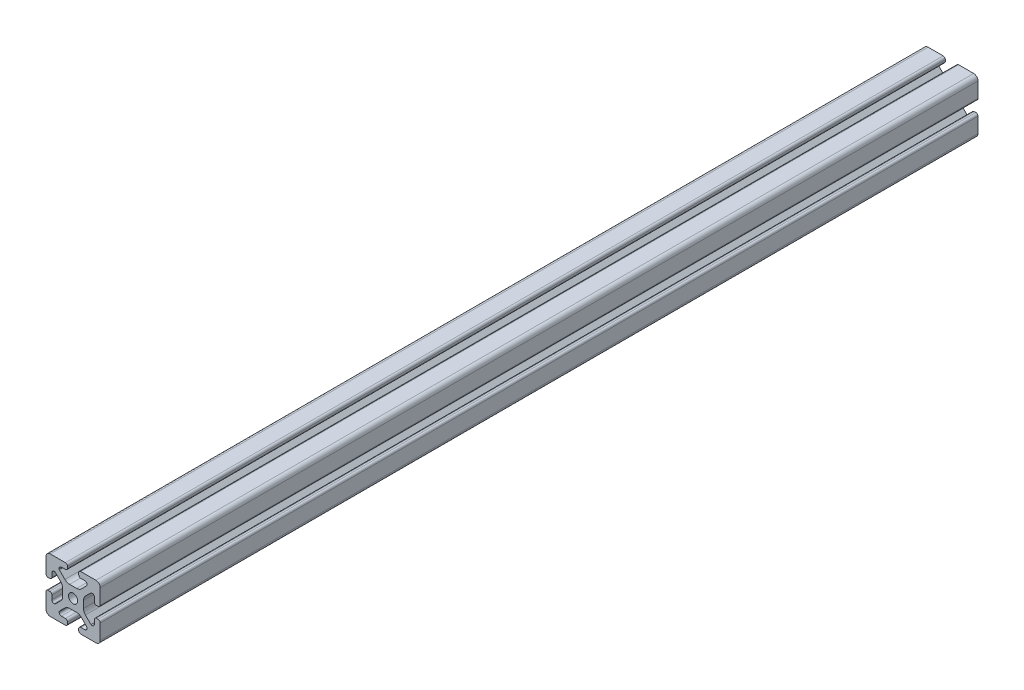
SolidWorks part; units mm, degrees
ref_plane "Front Plane" through (0, 0, 0) normal (0, 0, 1) x (1, 0, 0)
ref_plane "Top Plane" through (0, 0, 0) normal (0, 1, 0) x (1, 0, 0)
ref_plane "Right Plane" through (0, 0, 0) normal (1, 0, 0) x (0, 0, -1)
ref_plane "Plane1" through (0, 0, -4000) normal (0, 0, -1) x (-1, 0, 0)
sketch "Sketch1" plane through (0, 0, -4000) normal (0, 0, -1) x (-1, 0, 0)
  line L0 (16.83, 20) -> (5.6904, 20)
  line L1 (4.1204, 18.43) -> (4.1204, 17.25)
  line L2 (5.6904, 15.68) -> (8.7154, 15.68)
  line L3 (10.2854, 14.11) -> (10.2854, 13.6549)
  line L4 (10.0628, 13.1175) -> (6.0551, 9.1098)
  line L5 (2.6153, 7.685) -> (-2.6153, 7.685)
  line L6 (-6.0551, 9.1098) -> (-10.0628, 13.1175)
  line L7 (-10.2854, 13.6549) -> (-10.2854, 14.11)
  line L8 (-8.7154, 15.68) -> (-5.6904, 15.68)
  line L9 (-4.1204, 17.25) -> (-4.1204, 18.43)
  line L10 (-5.6904, 20) -> (-16.83, 20)
  line L11 (-20, 16.83) -> (-20, 5.6904)
  line L12 (-18.43, 4.1204) -> (-17.25, 4.1204)
  line L13 (-15.68, 5.6904) -> (-15.68, 8.7154)
  line L14 (-14.11, 10.2854) -> (-13.6549, 10.2854)
  line L15 (-13.1175, 10.0628) -> (-9.1098, 6.0551)
  line L16 (-7.685, 2.6153) -> (-7.685, -2.6153)
  line L17 (-9.1098, -6.0551) -> (-13.1175, -10.0628)
  line L18 (-13.6549, -10.2854) -> (-14.11, -10.2854)
  line L19 (-15.68, -8.7154) -> (-15.68, -5.6904)
  line L20 (-17.25, -4.1204) -> (-18.43, -4.1204)
  line L21 (-20, -5.6904) -> (-20, -16.83)
  line L22 (-16.83, -20) -> (-5.6904, -20)
  line L23 (-4.1204, -18.43) -> (-4.1204, -17.25)
  line L24 (-5.6904, -15.68) -> (-8.7154, -15.68)
  line L25 (-10.2854, -14.11) -> (-10.2854, -13.6549)
  line L26 (-10.0628, -13.1175) -> (-6.0551, -9.1098)
  line L27 (-2.6153, -7.685) -> (2.6153, -7.685)
  line L28 (6.0551, -9.1098) -> (10.0628, -13.1175)
  line L29 (10.2854, -13.6549) -> (10.2854, -14.11)
  line L30 (8.7154, -15.68) -> (5.6904, -15.68)
  line L31 (4.1204, -17.25) -> (4.1204, -18.43)
  line L32 (5.6904, -20) -> (16.83, -20)
  line L33 (20, -16.83) -> (20, -5.6904)
  line L34 (18.43, -4.1204) -> (17.25, -4.1204)
  line L35 (15.68, -5.6904) -> (15.68, -8.7154)
  line L36 (14.11, -10.2854) -> (13.6549, -10.2854)
  line L37 (13.1175, -10.0628) -> (9.1098, -6.0551)
  line L38 (7.685, -2.6153) -> (7.685, 2.6153)
  line L39 (9.1098, 6.0551) -> (13.1175, 10.0628)
  line L40 (13.6549, 10.2854) -> (14.11, 10.2854)
  line L41 (15.68, 8.7154) -> (15.68, 5.6904)
  line L42 (17.25, 4.1204) -> (18.43, 4.1204)
  line L43 (20, 5.6904) -> (20, 16.83)
  circle A0 centre (0, 0) radius 3.4
  arc A1 (20, 16.83) -> (16.83, 20) centre (16.83, 16.83) ccw
  arc A2 (5.6904, 20) -> (4.1204, 18.43) centre (5.6904, 18.43) ccw
  arc A3 (4.1204, 17.25) -> (5.6904, 15.68) centre (5.6904, 17.25) ccw
  arc A4 (8.7154, 15.68) -> (10.2854, 14.11) centre (8.7154, 14.11) cw
  arc A5 (10.2854, 13.6549) -> (10.0628, 13.1175) centre (9.5254, 13.6549) cw
  arc A6 (6.0551, 9.1098) -> (2.6153, 7.685) centre (2.6153, 12.5496) cw
  arc A7 (-2.6153, 7.685) -> (-6.0551, 9.1098) centre (-2.6153, 12.5496) cw
  arc A8 (-10.0628, 13.1175) -> (-10.2854, 13.6549) centre (-9.5254, 13.6549) cw
  arc A9 (-10.2854, 14.11) -> (-8.7154, 15.68) centre (-8.7154, 14.11) cw
  arc A10 (-5.6904, 15.68) -> (-4.1204, 17.25) centre (-5.6904, 17.25) ccw
  arc A11 (-4.1204, 18.43) -> (-5.6904, 20) centre (-5.6904, 18.43) ccw
  arc A12 (-16.83, 20) -> (-20, 16.83) centre (-16.83, 16.83) ccw
  arc A13 (-20, 5.6904) -> (-18.43, 4.1204) centre (-18.43, 5.6904) ccw
  arc A14 (-17.25, 4.1204) -> (-15.68, 5.6904) centre (-17.25, 5.6904) ccw
  arc A15 (-15.68, 8.7154) -> (-14.11, 10.2854) centre (-14.11, 8.7154) cw
  arc A16 (-13.6549, 10.2854) -> (-13.1175, 10.0628) centre (-13.6549, 9.5254) cw
  arc A17 (-9.1098, 6.0551) -> (-7.685, 2.6153) centre (-12.5496, 2.6153) cw
  arc A18 (-7.685, -2.6153) -> (-9.1098, -6.0551) centre (-12.5496, -2.6153) cw
  arc A19 (-13.1175, -10.0628) -> (-13.6549, -10.2854) centre (-13.6549, -9.5254) cw
  arc A20 (-14.11, -10.2854) -> (-15.68, -8.7154) centre (-14.11, -8.7154) cw
  arc A21 (-15.68, -5.6904) -> (-17.25, -4.1204) centre (-17.25, -5.6904) ccw
  arc A22 (-18.43, -4.1204) -> (-20, -5.6904) centre (-18.43, -5.6904) ccw
  arc A23 (-20, -16.83) -> (-16.83, -20) centre (-16.83, -16.83) ccw
  arc A24 (-5.6904, -20) -> (-4.1204, -18.43) centre (-5.6904, -18.43) ccw
  arc A25 (-4.1204, -17.25) -> (-5.6904, -15.68) centre (-5.6904, -17.25) ccw
  arc A26 (-8.7154, -15.68) -> (-10.2854, -14.11) centre (-8.7154, -14.11) cw
  arc A27 (-10.2854, -13.6549) -> (-10.0628, -13.1175) centre (-9.5254, -13.6549) cw
  arc A28 (-6.0551, -9.1098) -> (-2.6153, -7.685) centre (-2.6153, -12.5496) cw
  arc A29 (2.6153, -7.685) -> (6.0551, -9.1098) centre (2.6153, -12.5496) cw
  arc A30 (10.0628, -13.1175) -> (10.2854, -13.6549) centre (9.5254, -13.6549) cw
  arc A31 (10.2854, -14.11) -> (8.7154, -15.68) centre (8.7154, -14.11) cw
  arc A32 (5.6904, -15.68) -> (4.1204, -17.25) centre (5.6904, -17.25) ccw
  arc A33 (4.1204, -18.43) -> (5.6904, -20) centre (5.6904, -18.43) ccw
  arc A34 (16.83, -20) -> (20, -16.83) centre (16.83, -16.83) ccw
  arc A35 (20, -5.6904) -> (18.43, -4.1204) centre (18.43, -5.6904) ccw
  arc A36 (17.25, -4.1204) -> (15.68, -5.6904) centre (17.25, -5.6904) ccw
  arc A37 (15.68, -8.7154) -> (14.11, -10.2854) centre (14.11, -8.7154) cw
  arc A38 (13.6549, -10.2854) -> (13.1175, -10.0628) centre (13.6549, -9.5254) cw
  arc A39 (9.1098, -6.0551) -> (7.685, -2.6153) centre (12.5496, -2.6153) cw
  arc A40 (7.685, 2.6153) -> (9.1098, 6.0551) centre (12.5496, 2.6153) cw
  arc A41 (13.1175, 10.0628) -> (13.6549, 10.2854) centre (13.6549, 9.5254) cw
  arc A42 (14.11, 10.2854) -> (15.68, 8.7154) centre (14.11, 8.7154) cw
  arc A43 (15.68, 5.6904) -> (17.25, 4.1204) centre (17.25, 5.6904) ccw
  arc A44 (18.43, 4.1204) -> (20, 5.6904) centre (18.43, 5.6904) ccw
extrude "Boss-Extrude1" add sketch "Sketch1" against normal blind 4000
ref_plane "Plane2" through (0, 0, -647.7) normal (0, 0, 1) x (1, 0, 0)
sketch "Sketch2" plane through (0, 0, -647.7) normal (0, 0, 1) x (1, 0, 0)
  line L1 (-120.2246, 91.3579) -> (120.2246, 91.3579)
  line L2 (-120.2246, 91.3579) -> (-120.2246, -91.3579)
  line L3 (-120.2246, -91.3579) -> (120.2246, -91.3579)
  line L4 (120.2246, 91.3579) -> (120.2246, -91.3579)
  line L5 (-120.2246, 91.3579) -> (120.2246, -91.3579) construction
  line L6 (-120.2246, -91.3579) -> (120.2246, 91.3579) construction
  point P0 (0, 0)
  point P6 (120.2246, -91.3579)
extrude "Cut-Extrude1" cut sketch "Sketch2" against normal through all
